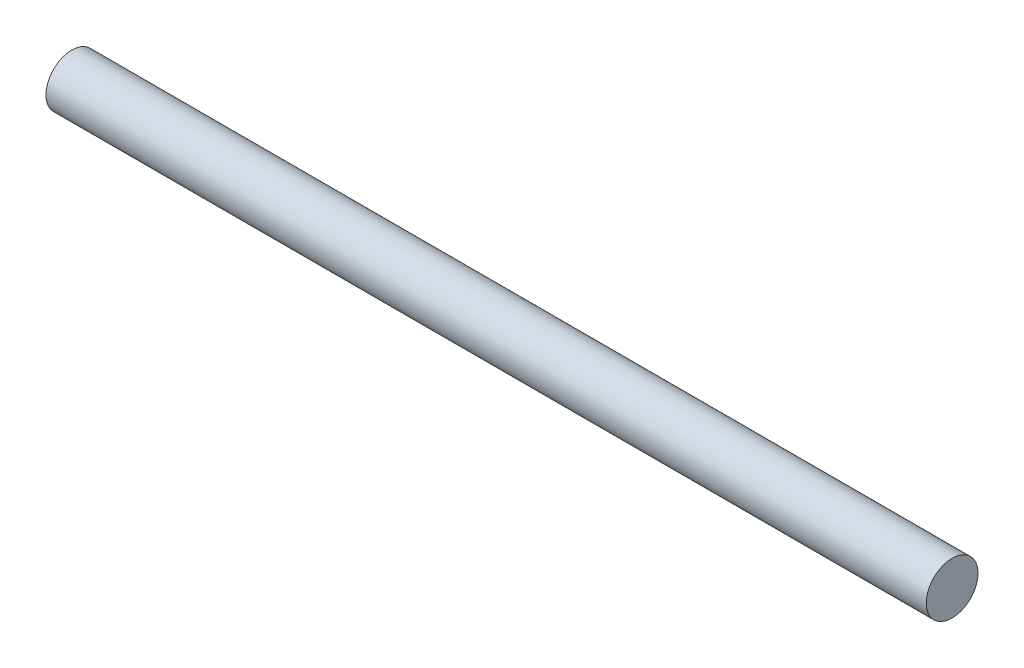
SolidWorks part; units mm, degrees
ref_plane "Front Plane" through (0, 0, 0) normal (0, 0, 1) x (1, 0, 0)
ref_plane "Top Plane" through (0, 0, 0) normal (0, 1, 0) x (1, 0, 0)
ref_plane "Right Plane" through (0, 0, 0) normal (1, 0, 0) x (0, 0, -1)
sketch "Sketch1" plane through (0, 0, 0) normal (1, 0, 0) x (0, 0, -1)
  circle A0 centre (0, 0) radius 3
  dimension "D1" = 6
extrude "Boss-Extrude1" add sketch "Sketch1" along normal blind 102
